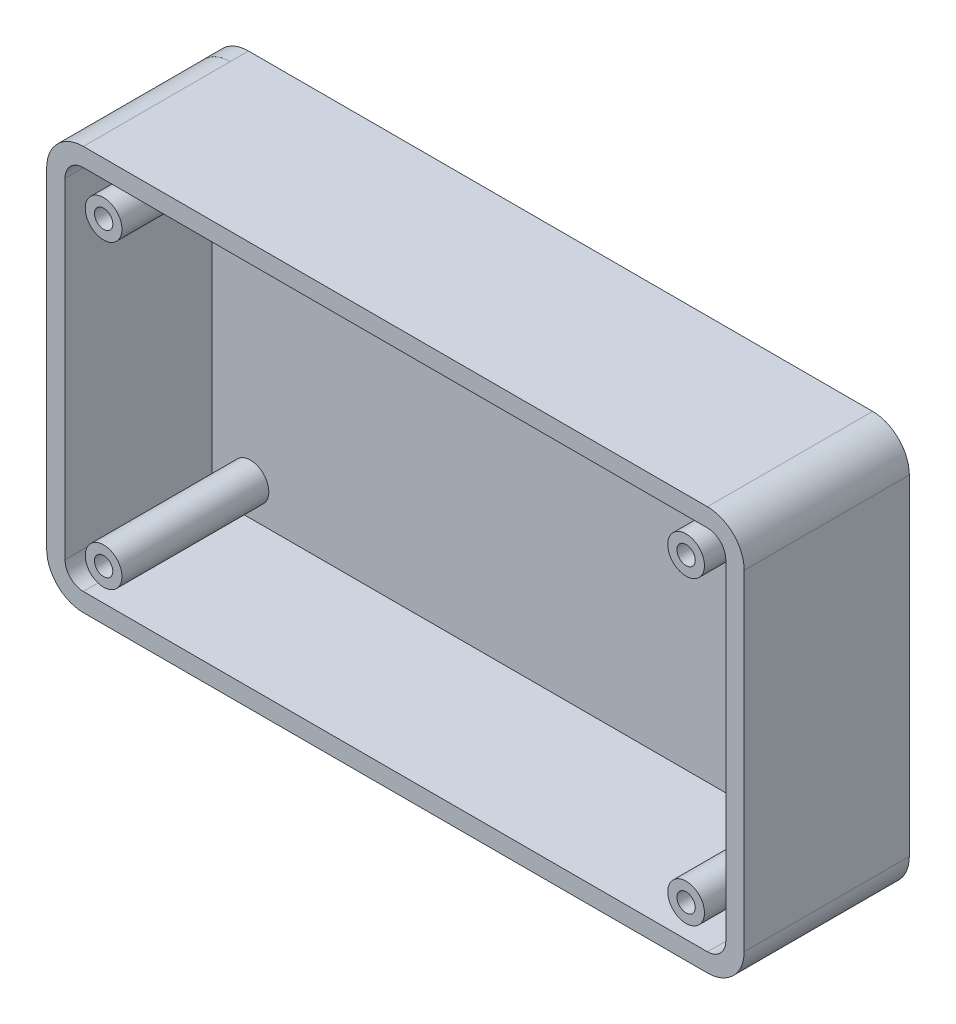
SolidWorks part; units mm, degrees
ref_plane "Front Plane" through (0, 0, 0) normal (0, 0, 1) x (1, 0, 0)
ref_plane "Top Plane" through (0, 0, 0) normal (0, 1, 0) x (1, 0, 0)
ref_plane "Right Plane" through (0, 0, 0) normal (1, 0, 0) x (0, 0, -1)
sketch "Sketch1" plane through (0, 0, 0) normal (0, 0, 1) x (1, 0, 0)
  line L0 (-95, -45) -> (-95, 45)
  line L1 (-85, -50) -> (85, -50)
  line L2 (-90, -45) -> (-90, 45)
  line L3 (-85, 50) -> (85, 50)
  line L4 (90, -45) -> (90, 45)
  line L7 (-85, 55) -> (85, 55)
  line L8 (95, -45) -> (95, 45)
  line L9 (-85, -55) -> (85, -55)
  arc A0 (90, 45) -> (85, 50) centre (85, 45) ccw
  arc A1 (90, -45) -> (85, -50) centre (85, -45) cw
  arc A2 (-90, -45) -> (-85, -50) centre (-85, -45) ccw
  arc A3 (-85, 50) -> (-90, 45) centre (-85, 45) ccw
  arc A4 (-85, 55) -> (-95, 45) centre (-85, 45) ccw
  arc A5 (95, 45) -> (85, 55) centre (85, 45) ccw
  arc A6 (95, -45) -> (85, -55) centre (85, -45) cw
  arc A7 (-95, -45) -> (-85, -55) centre (-85, -45) ccw
  point P0 (0, 0)
  dimension "D3" = 5
  dimension "D4" = 5
extrude "Boss-Extrude1" add sketch "Sketch1" along normal blind 40
sketch "Sketch2" plane through (0, 0, 0) normal (0, 0, -1) x (-1, 0, 0)
  point P0 (0, 0)
  point P1 (0, 0)
sketch "Sketch3" plane through (0, 0, 0) normal (0, 0, -1) x (-1, 0, 0)
  line L1 (-85, -55) -> (85.0258, -55)
  line L2 (-95, -45) -> (-95, 45)
  line L3 (-85, 55) -> (85.0258, 55)
  line L4 (95.0258, -45) -> (95.0258, 45)
  arc A0 (95.0258, 45) -> (85.0258, 55) centre (85.0258, 45) ccw
  arc A1 (95.0258, -45) -> (85.0258, -55) centre (85.0258, -45) cw
  arc A2 (-85, -55) -> (-95, -45) centre (-85, -45) cw
  arc A3 (-95, 45) -> (-85, 55) centre (-85, 45) cw
  point P10 (-95, -55)
  point P13 (-95, 55)
  dimension "D2" = 10
  dimension "D1" = 110
extrude "Boss-Extrude2" add sketch "Sketch3" along normal blind 5
sketch "Sketch4" plane through (0, 0, 0) normal (0, 0, 1) x (1, 0, 0)
  circle A0 centre (-79.4849, 40.6919) radius 5
  circle A2 centre (-79.4849, -41.2381) radius 5
  circle A3 centre (79.186, -41.2381) radius 5
  circle A4 centre (79.186, 40.6919) radius 5
  circle A5 centre (-79.4849, 40.6919) radius 2.5
  circle A6 centre (79.186, 40.6919) radius 2.5
  circle A7 centre (-79.4849, -41.2381) radius 2.5
  circle A8 centre (79.186, -41.2381) radius 2.5
  dimension "D1" = 10
  dimension "D2" = 10
  dimension "D3" = 10
  dimension "D4" = 10
  dimension "D5" = 158.671
  dimension "D6" = 81.9299
extrude "Boss-Extrude3" add sketch "Sketch4" along normal blind 40
sketch "Sketch5" plane through (0, 0, 40) normal (0, 0, 1) x (1, 0, 0)
  circle A0 centre (-79.4849, 40.6919) radius 2.5
  circle A1 centre (79.186, 40.6919) radius 2.4566
  circle A2 centre (-79.4849, -41.2381) radius 2.5
  circle A3 centre (79.186, -41.2381) radius 2.5
extrude "Cut-Extrude2" cut sketch "Sketch5" against normal blind 60
